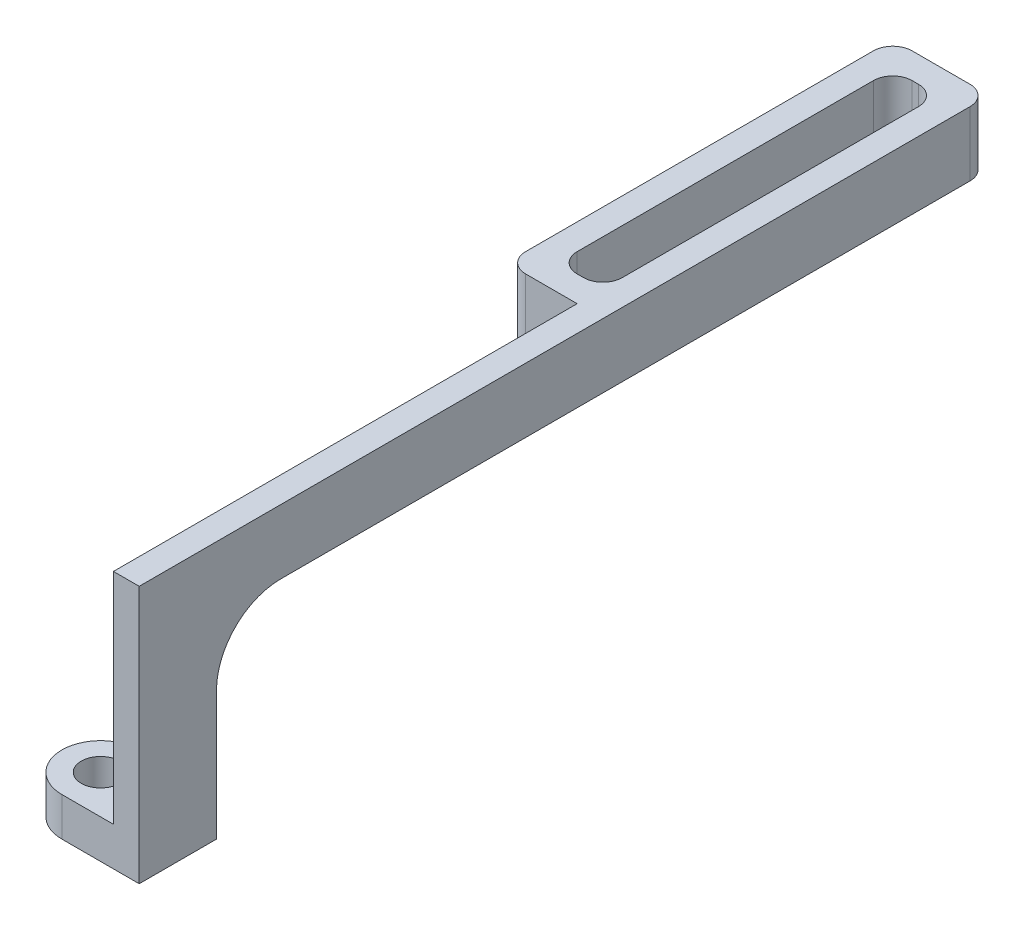
SolidWorks part; units mm, degrees
ref_plane "前视基准面" through (0, 0, 0) normal (0, 0, 1) x (1, 0, 0)
ref_plane "上视基准面" through (0, 0, 0) normal (0, 1, 0) x (1, 0, 0)
ref_plane "右视基准面" through (0, 0, 0) normal (1, 0, 0) x (0, 0, -1)
other "Configuration Table"
sketch "草图1" plane through (0, 0, 0) normal (0, 1, 0) x (1, 0, 0)
  line L0 (0, 3) -> (6, 3)
  line L1 (0, -3) -> (6, -3)
  line L2 (6, -3) -> (6, 3)
  circle A0 centre (0, 0) radius 1.5
  circle A1 centre (0, 0) radius 3
  dimension "D1" = 3
  dimension "D2" = 6
  dimension "D3" = 6
extrude "凸台-拉伸1" add sketch "草图1" along normal blind 3 contours A1 A0 | A1 L1 L2 L0
sketch "草图2" plane through (0, 0, 0) normal (0, 1, 0) x (1, 0, 0)
  line L0 (4, 3) -> (6, 3)
  line L1 (0, 3) -> (6, 3) construction
  line L2 (6, 3) -> (6, -3)
  line L3 (6, -3) -> (4, -3)
  line L4 (0, -3) -> (6, -3) construction
  line L5 (4, -3) -> (4, 3)
  dimension "D1" = 2
extrude "凸台-拉伸2" add sketch "草图2" along normal blind 15
ref_plane "基准面1" through (0, 15, 0) normal (0, 1, 0) x (1, 0, 0)
sketch "草图3" plane through (0, 15, 0) normal (0, 1, 0) x (1, 0, 0)
  line L0 (6, -3) -> (6, 63)
  line L1 (6, -3) -> (4, -3)
  line L2 (4, -3) -> (4, 33)
  line L3 (4, 63) -> (6, 63)
  line L4 (4, 63) -> (-1.5, 63)
  line L5 (-1.5, 63) -> (-1.5, 33)
  line L6 (-1.5, 33) -> (4, 33)
  line L7 (4, 61) -> (0.5, 61)
  line L8 (0.5, 61) -> (0.5, 35)
  line L9 (0.5, 35) -> (4, 35)
  line L10 (4, 35) -> (4, 61)
  point P13 (2.25, 61)
  dimension "D1" = 66
  dimension "D2" = 3.5
  dimension "D3" = 2
  dimension "D4" = 30
  dimension "D5" = 2
  dimension "D6" = 2
extrude "凸台-拉伸3" add sketch "草图3" along normal blind 5
fillet "圆角1" radius 5 1 edges at (5, 15, -3)
fillet "圆角2" radius 1.5 5 edges at (-1.5, 17.5, -33) (6, 17.5, -63) (-1.5, 17.5, -63) (4, 17.5, -35) (0.5, 17.5, -35)
fillet "圆角3" radius 1.5 2 edges at (0.5, 17.5, -61) (4, 17.5, -61)
